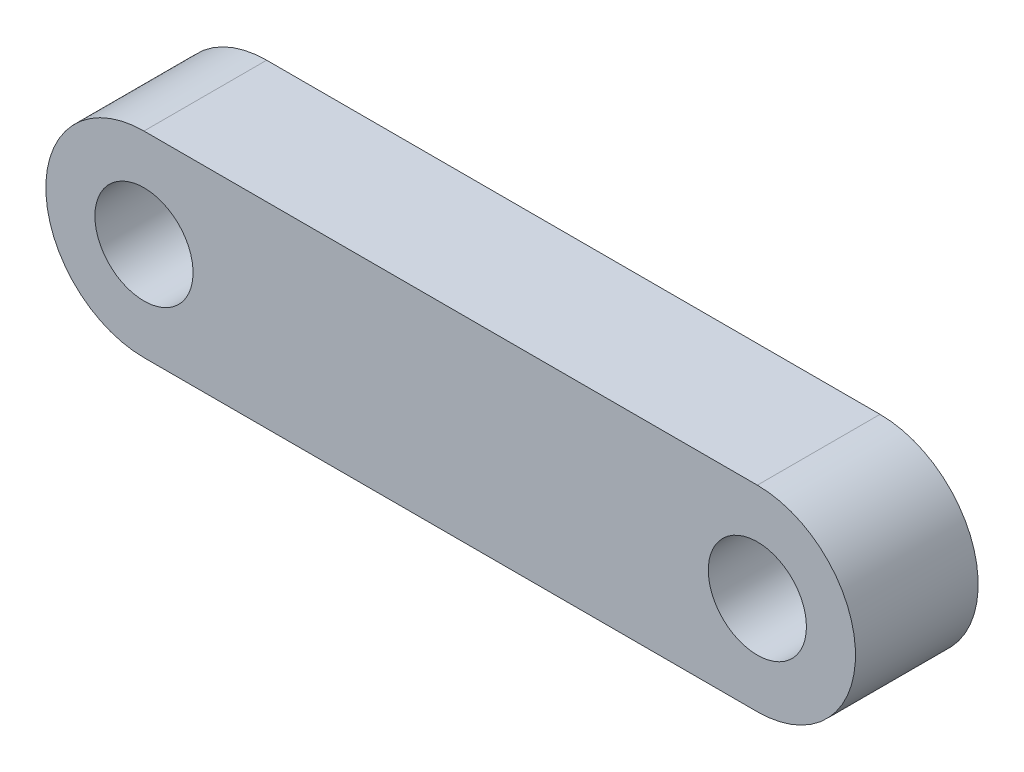
SolidWorks part; units mm, degrees
ref_plane "Front Plane" through (0, 0, 0) normal (0, 0, 1) x (1, 0, 0)
ref_plane "Top Plane" through (0, 0, 0) normal (0, 1, 0) x (1, 0, 0)
ref_plane "Right Plane" through (0, 0, 0) normal (1, 0, 0) x (0, 0, -1)
sketch "Sketch1" plane through (0, 0, 0) normal (0, 0, 1) x (1, 0, 0)
  line L0 (-12.5, 0) -> (12.5, 0) construction
  line L1 (-12.5, 4) -> (12.5, 4)
  line L2 (-12.5, -4) -> (12.5, -4)
  line L3 (0, -1000) -> (0, 49000) construction
  arc A0 (-12.5, 4) -> (-12.5, -4) centre (-12.5, 0) ccw
  arc A1 (12.5, -4) -> (12.5, 4) centre (12.5, 0) ccw
  circle A2 centre (12.5, 0) radius 2
  circle A3 centre (-12.5, 0) radius 2
  point P3 (0, 0)
  dimension "D2" = 4
  dimension "D1" = 25
extrude "Boss-Extrude1" add sketch "Sketch1" along normal blind 5
